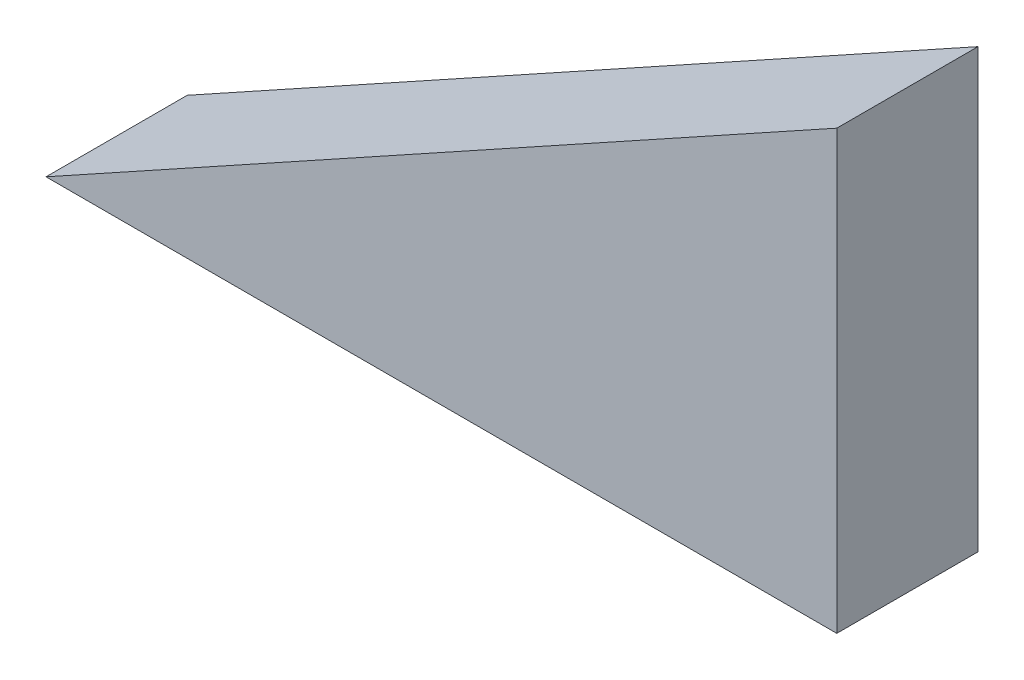
SolidWorks part; units mm, degrees
ref_plane "Front Plane" through (0, 0, 0) normal (0, 0, 1) x (1, 0, 0)
ref_plane "Top Plane" through (0, 0, 0) normal (0, 1, 0) x (1, 0, 0)
ref_plane "Right Plane" through (0, 0, 0) normal (1, 0, 0) x (0, 0, -1)
sketch "Sketch1" plane through (0, 0, 0) normal (0, 0, 1) x (1, 0, 0)
  line L0 (0, 0) -> (28, 0)
  line L1 (28, 0) -> (28, 15.4919)
  line L2 (28, 15.4919) -> (0, 0)
  dimension "D1" = 32
  dimension "D2" = 28
extrude "Boss-Extrude1" add sketch "Sketch1" along normal blind 5
